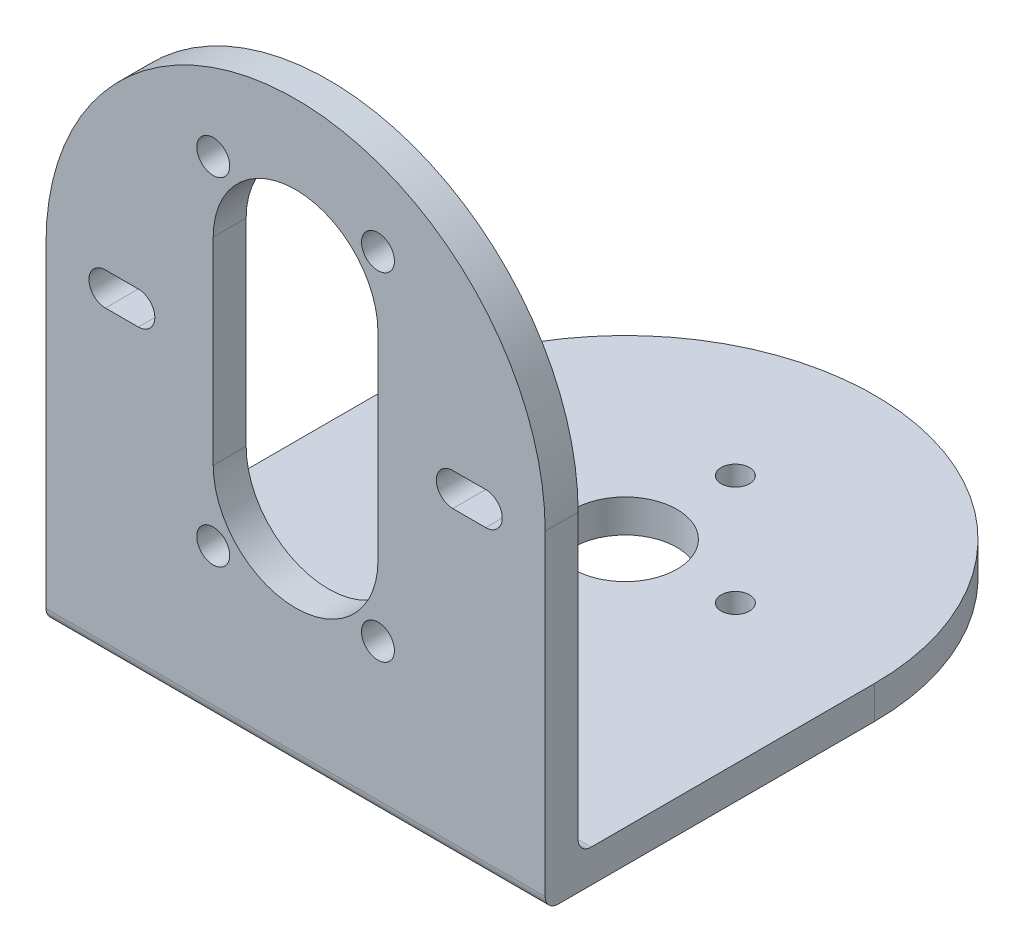
SolidWorks part; units mm, degrees
material "1060 Alloy"
ref_plane "Front" through (0, 0, 0) normal (0, 0, 1) x (1, 0, 0)
ref_plane "Top" through (0, 0, 0) normal (0, 1, 0) x (1, 0, 0)
ref_plane "Right" through (0, 0, 0) normal (1, 0, 0) x (0, 0, -1)
sketch "Sketch1" plane through (0, 0, 0) normal (0, 1, 0) x (1, 0, 0)
  line L0 (-19.24, 0) -> (-19.24, -25.4)
  line L1 (19.24, 0) -> (19.24, -25.4)
  line L2 (19.24, -25.4) -> (-19.24, -25.4)
  arc A0 (19.24, 0) -> (-19.24, 0) centre (0, 0) ccw
  circle A1 centre (0, 0) radius 4
  dimension "D1" = 38.48
  dimension "D2" = 8
  dimension "D3" = 25.4
extrude "Boss-Extrude1" add sketch "Sketch1" along normal blind 2.54
ref_plane "Plane1" through (0, 2.54, 0) normal (0, 1, 0) x (1, 0, 0)
sketch "Sketch2" plane through (0, 2.54, 0) normal (0, 1, 0) x (1, 0, 0)
  line L0 (-19.24, -25.4) -> (19.24, -25.4) construction
  circle A0 centre (0, 8.5) radius 1.09
  circle A1 centre (0, 0) radius 4 construction
  dimension "D1" = 2.18
  dimension "D2" = 8.5
  dimension "D3" = 33.9
extrude "Cut-Extrude1" cut sketch "Sketch2" against normal mid plane 10
pattern_circular "CirPattern1" count 4 over 360 about axis through (0, 0, 0) along (0, 1, 0) of "Cut-Extrude1"
ref_plane "Plane2" through (0, 0, 25.4) normal (0, 0, 1) x (1, 0, 0)
sketch "Sketch3" plane through (0, 0, 25.4) normal (0, 0, 1) x (1, 0, 0)
  line L0 (19.24, 2.54) -> (19.24, 25.4)
  line L1 (21.164, 2.54) -> (-21.164, 2.54) construction
  line L2 (19.24, 2.54) -> (19.24, 0) construction
  line L3 (-19.24, 2.54) -> (-19.24, 25.4)
  line L4 (0, 44.64) -> (0, 0) construction
  line L5 (6.35, 32.24) -> (6.35, 17)
  line L6 (-6.35, 32.24) -> (-6.35, 17)
  line L7 (6.35, 37.62) -> (6.35, 11.62) construction
  line L8 (6.35, 24.62) -> (-6.35, 24.62) construction
  line L9 (14.66, 25.89) -> (12.12, 25.89)
  line L10 (14.66, 23.35) -> (12.12, 23.35)
  line L11 (-14.66, 23.35) -> (-12.12, 23.35)
  line L12 (-14.66, 25.89) -> (-12.12, 25.89)
  line L13 (19.24, 2.54) -> (-19.24, 2.54)
  arc A0 (19.24, 25.4) -> (-19.24, 25.4) centre (0, 25.4) ccw
  arc A1 (6.35, 32.24) -> (-6.35, 32.24) centre (0, 32.24) ccw
  arc A2 (6.35, 17) -> (-6.35, 17) centre (0, 17) cw
  circle A3 centre (6.35, 37.62) radius 1.27
  circle A4 centre (6.35, 11.62) radius 1.27
  circle A5 centre (-6.35, 11.62) radius 1.27
  circle A6 centre (-6.35, 37.62) radius 1.27
  arc A7 (12.12, 25.89) -> (12.12, 23.35) centre (12.12, 24.62) ccw
  arc A8 (14.66, 25.89) -> (14.66, 23.35) centre (14.66, 24.62) cw
  arc A9 (-14.66, 25.89) -> (-14.66, 23.35) centre (-14.66, 24.62) ccw
  arc A10 (-12.12, 25.89) -> (-12.12, 23.35) centre (-12.12, 24.62) cw
  point P25 (6.35, 24.62)
  point P36 (10.85, 24.62)
  point P43 (-10.85, 24.62)
  dimension "D5" = 2.54
  dimension "D1" = 22.86
  dimension "D2" = 15.24
  dimension "D3" = 12.7
  dimension "D4" = 17
  dimension "D6" = 26
  dimension "D7" = 2.54
  dimension "D8" = 2.54
  dimension "D9" = 4.5
extrude "Boss-Extrude2" add sketch "Sketch3" against normal blind 2.54
fillet "Fillet1" radius 1 2 edges at (0, 0, 25.4)
